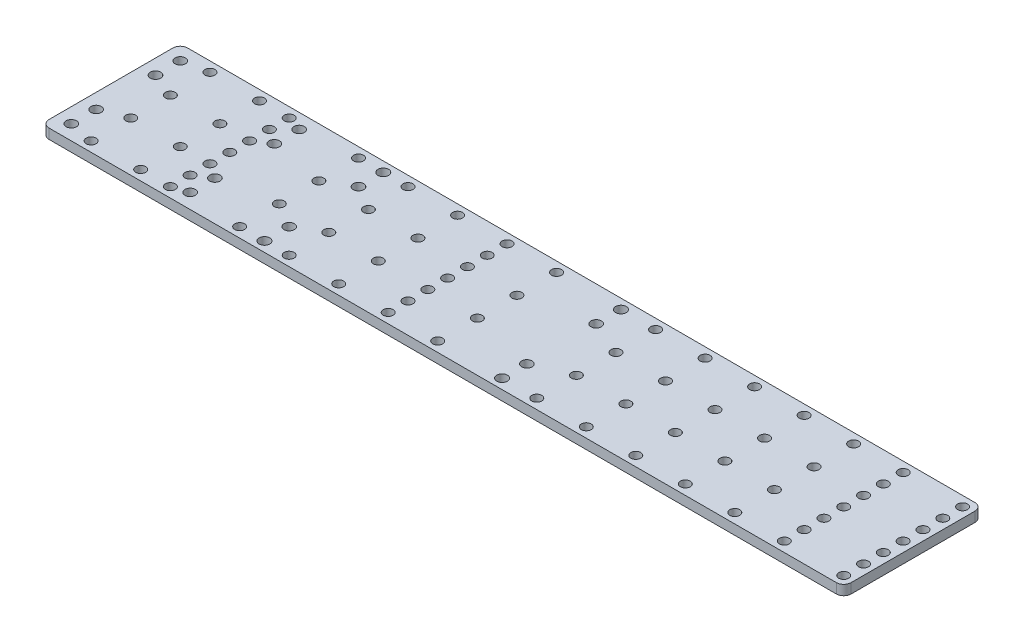
SolidWorks part; units mm, degrees
material "Thornel Mat VMA"
ref_plane "前视基准面" through (0, 0, 0) normal (0, 0, 1) x (1, 0, 0)
ref_plane "上视基准面" through (0, 0, 0) normal (0, 1, 0) x (1, 0, 0)
ref_plane "右视基准面" through (0, 0, 0) normal (1, 0, 0) x (0, 0, -1)
other "Configuration Table"
sketch "草图1" plane through (0, 0, 0) normal (0, 1, 0) x (1, 0, 0)
  line L1 (0, 0) -> (324, 0)
  line L2 (0, 0) -> (0, 56)
  line L3 (0, 56) -> (324, 56)
  line L4 (324, 0) -> (324, 56)
  dimension "D1" = 56
  dimension "D2" = 324
extrude "凸台-拉伸1" add sketch "草图1" along normal blind 4
sketch "草图2" plane through (0, 4, 0) normal (0, 1, 0) x (1, 0, 0)
  arc A4 (294, 44) -> (298, 44) centre (296, 44) ccw
  arc A5 (298, 44) -> (294, 44) centre (296, 44) ccw
  arc A8 (294, 52) -> (298, 52) centre (296, 52) ccw
  arc A9 (298, 52) -> (294, 52) centre (296, 52) ccw
  arc A12 (294, 12) -> (298, 12) centre (296, 12) ccw
  arc A13 (298, 12) -> (294, 12) centre (296, 12) ccw
  arc A16 (294, 4) -> (298, 4) centre (296, 4) ccw
  arc A17 (298, 4) -> (294, 4) centre (296, 4) ccw
  arc A20 (294, 20) -> (298, 20) centre (296, 20) ccw
  arc A21 (298, 20) -> (294, 20) centre (296, 20) ccw
  arc A24 (294, 28) -> (298, 28) centre (296, 28) ccw
  arc A25 (298, 28) -> (294, 28) centre (296, 28) ccw
  arc A28 (294, 36) -> (298, 36) centre (296, 36) ccw
  arc A29 (298, 36) -> (294, 36) centre (296, 36) ccw
  arc A32 (134, 44) -> (138, 44) centre (136, 44) ccw
  arc A33 (138, 44) -> (134, 44) centre (136, 44) ccw
  arc A36 (134, 52) -> (138, 52) centre (136, 52) ccw
  arc A37 (138, 52) -> (134, 52) centre (136, 52) ccw
  arc A40 (134, 12) -> (138, 12) centre (136, 12) ccw
  arc A41 (138, 12) -> (134, 12) centre (136, 12) ccw
  arc A44 (134, 4) -> (138, 4) centre (136, 4) ccw
  arc A45 (138, 4) -> (134, 4) centre (136, 4) ccw
  arc A48 (134, 20) -> (138, 20) centre (136, 20) ccw
  arc A49 (138, 20) -> (134, 20) centre (136, 20) ccw
  arc A52 (134, 28) -> (138, 28) centre (136, 28) ccw
  arc A53 (138, 28) -> (134, 28) centre (136, 28) ccw
  arc A56 (134, 36) -> (138, 36) centre (136, 36) ccw
  arc A57 (138, 36) -> (134, 36) centre (136, 36) ccw
  arc A60 (46, 44) -> (50, 44) centre (48, 44) ccw
  arc A61 (50, 44) -> (46, 44) centre (48, 44) ccw
  arc A64 (46, 52) -> (50, 52) centre (48, 52) ccw
  arc A65 (50, 52) -> (46, 52) centre (48, 52) ccw
  arc A68 (46, 12) -> (50, 12) centre (48, 12) ccw
  arc A69 (50, 12) -> (46, 12) centre (48, 12) ccw
  arc A72 (46, 4) -> (50, 4) centre (48, 4) ccw
  arc A73 (50, 4) -> (46, 4) centre (48, 4) ccw
  arc A76 (46, 20) -> (50, 20) centre (48, 20) ccw
  arc A77 (50, 20) -> (46, 20) centre (48, 20) ccw
  arc A80 (46, 28) -> (50, 28) centre (48, 28) ccw
  arc A81 (50, 28) -> (46, 28) centre (48, 28) ccw
  arc A84 (46, 36) -> (50, 36) centre (48, 36) ccw
  arc A85 (50, 36) -> (46, 36) centre (48, 36) ccw
extrude "切除-拉伸1" cut sketch "草图2" against normal blind 10
sketch "草图3" plane through (0, 4, 0) normal (0, 1, 0) x (1, 0, 0)
  circle A4 centre (182, 52) radius 2.15
  circle A5 centre (182, 42) radius 2.1
  circle A6 centre (182, 14) radius 2.1
  circle A7 centre (182, 4) radius 2.15
  circle A12 centre (86, 52) radius 2.15
  circle A13 centre (86, 4) radius 2.15
  circle A14 centre (86, 42) radius 2.1
  circle A15 centre (86, 14) radius 2.1
  circle A24 centre (6, 6) radius 2.1
  circle A25 centre (6, 16) radius 2.1
  circle A26 centre (6, 40) radius 2.1
  circle A27 centre (6, 50) radius 2.1
  circle A28 centre (54, 50) radius 2.1
  circle A29 centre (54, 40) radius 2.1
  circle A30 centre (54, 6) radius 2.1
  circle A31 centre (54, 16) radius 2.1
extrude "切除-拉伸2" cut sketch "草图3" against normal through all both
sketch "草图4" plane through (0, 4, 0) normal (0, 1, 0) x (1, 0, 0)
  circle A0 centre (296, 4) radius 2 construction
  circle A1 centre (296, 12) radius 2 construction
  circle A2 centre (296, 20) radius 2 construction
  circle A3 centre (296, 28) radius 2 construction
  circle A4 centre (296, 36) radius 2 construction
  circle A5 centre (296, 44) radius 2 construction
  circle A6 centre (296, 52) radius 2 construction
  circle A7 centre (296, 4) radius 2
  circle A8 centre (296, 12) radius 2 construction
  circle A9 centre (296, 20) radius 2
  circle A10 centre (296, 28) radius 2 construction
  circle A11 centre (296, 36) radius 2
  circle A12 centre (296, 44) radius 2 construction
  circle A13 centre (296, 52) radius 2
  circle A14 centre (316, 4) radius 2 construction
  circle A15 centre (316, 20) radius 2 construction
  circle A16 centre (316, 36) radius 2 construction
  circle A17 centre (316, 52) radius 2 construction
  circle A18 centre (316, 12) radius 2 construction
  circle A19 centre (316, 28) radius 2 construction
  circle A20 centre (316, 44) radius 2 construction
  circle A21 centre (276, 4) radius 2
  circle A22 centre (276, 20) radius 2
  circle A23 centre (276, 36) radius 2
  circle A24 centre (276, 52) radius 2
  circle A25 centre (276, 12) radius 2 construction
  circle A26 centre (276, 28) radius 2 construction
  circle A27 centre (276, 44) radius 2 construction
  circle A28 centre (256, 4) radius 2
  circle A29 centre (256, 20) radius 2
  circle A30 centre (256, 36) radius 2
  circle A31 centre (256, 52) radius 2
  circle A32 centre (256, 12) radius 2 construction
  circle A33 centre (256, 28) radius 2 construction
  circle A34 centre (256, 44) radius 2 construction
  circle A35 centre (236, 4) radius 2
  circle A36 centre (236, 20) radius 2
  circle A37 centre (236, 36) radius 2
  circle A38 centre (236, 52) radius 2
  circle A39 centre (236, 12) radius 2 construction
  circle A40 centre (236, 28) radius 2 construction
  circle A41 centre (236, 44) radius 2 construction
  circle A42 centre (216, 4) radius 2
  circle A43 centre (216, 20) radius 2
  circle A44 centre (216, 36) radius 2
  circle A45 centre (216, 52) radius 2
  circle A46 centre (216, 12) radius 2 construction
  circle A47 centre (216, 28) radius 2 construction
  circle A48 centre (216, 44) radius 2 construction
  circle A49 centre (196, 4) radius 2
  circle A50 centre (196, 20) radius 2
  circle A51 centre (196, 36) radius 2
  circle A52 centre (196, 52) radius 2
  circle A53 centre (196, 12) radius 2 construction
  circle A54 centre (196, 28) radius 2 construction
  circle A55 centre (196, 44) radius 2 construction
  circle A56 centre (176, 4) radius 2 construction
  circle A57 centre (176, 20) radius 2 construction
  circle A58 centre (176, 36) radius 2 construction
  circle A59 centre (176, 52) radius 2 construction
  circle A60 centre (176, 12) radius 2 construction
  circle A61 centre (176, 28) radius 2 construction
  circle A62 centre (176, 44) radius 2 construction
  circle A63 centre (156, 4) radius 2
  circle A64 centre (156, 20) radius 2
  circle A65 centre (156, 36) radius 2
  circle A66 centre (156, 52) radius 2
  circle A67 centre (156, 12) radius 2 construction
  circle A68 centre (156, 28) radius 2 construction
  circle A69 centre (156, 44) radius 2 construction
  circle A70 centre (136, 4) radius 2 construction
  circle A71 centre (136, 20) radius 2 construction
  circle A72 centre (136, 36) radius 2 construction
  circle A73 centre (136, 52) radius 2 construction
  circle A74 centre (136, 12) radius 2 construction
  circle A75 centre (136, 28) radius 2 construction
  circle A76 centre (136, 44) radius 2 construction
  circle A77 centre (116, 4) radius 2
  circle A78 centre (116, 20) radius 2
  circle A79 centre (116, 36) radius 2
  circle A80 centre (116, 52) radius 2
  circle A81 centre (116, 12) radius 2 construction
  circle A82 centre (116, 28) radius 2 construction
  circle A83 centre (116, 44) radius 2 construction
  circle A84 centre (96, 4) radius 2
  circle A85 centre (96, 20) radius 2
  circle A86 centre (96, 36) radius 2
  circle A87 centre (96, 52) radius 2
  circle A88 centre (96, 12) radius 2 construction
  circle A89 centre (96, 28) radius 2 construction
  circle A90 centre (96, 44) radius 2 construction
  circle A91 centre (76, 4) radius 2
  circle A92 centre (76, 20) radius 2
  circle A93 centre (76, 36) radius 2
  circle A94 centre (76, 52) radius 2
  circle A95 centre (76, 12) radius 2 construction
  circle A96 centre (76, 28) radius 2 construction
  circle A97 centre (76, 44) radius 2 construction
  circle A98 centre (56, 4) radius 2 construction
  circle A99 centre (56, 20) radius 2 construction
  circle A100 centre (56, 36) radius 2 construction
  circle A101 centre (56, 52) radius 2 construction
  circle A102 centre (56, 12) radius 2 construction
  circle A103 centre (56, 28) radius 2 construction
  circle A104 centre (56, 44) radius 2 construction
  circle A105 centre (36, 4) radius 2
  circle A106 centre (36, 20) radius 2
  circle A107 centre (36, 36) radius 2
  circle A108 centre (36, 52) radius 2
  circle A109 centre (36, 12) radius 2 construction
  circle A110 centre (36, 28) radius 2 construction
  circle A111 centre (36, 44) radius 2 construction
  circle A112 centre (16, 4) radius 2
  circle A113 centre (16, 20) radius 2
  circle A114 centre (16, 36) radius 2
  circle A115 centre (16, 52) radius 2
  circle A116 centre (16, 12) radius 2 construction
  circle A117 centre (16, 28) radius 2 construction
  circle A118 centre (16, 44) radius 2 construction
  arc A123 (318, 44) -> (322, 44) centre (320, 44) ccw
  arc A124 (322, 44) -> (318, 44) centre (320, 44) ccw
  arc A127 (318, 52) -> (322, 52) centre (320, 52) ccw
  arc A128 (322, 52) -> (318, 52) centre (320, 52) ccw
  arc A131 (318, 12) -> (322, 12) centre (320, 12) ccw
  arc A132 (322, 12) -> (318, 12) centre (320, 12) ccw
  arc A135 (318, 4) -> (322, 4) centre (320, 4) ccw
  arc A136 (322, 4) -> (318, 4) centre (320, 4) ccw
  arc A139 (318, 20) -> (322, 20) centre (320, 20) ccw
  arc A140 (322, 20) -> (318, 20) centre (320, 20) ccw
  arc A143 (318, 28) -> (322, 28) centre (320, 28) ccw
  arc A144 (322, 28) -> (318, 28) centre (320, 28) ccw
  arc A147 (318, 36) -> (322, 36) centre (320, 36) ccw
  arc A148 (322, 36) -> (318, 36) centre (320, 36) ccw
  dimension "D1" = 2
  dimension "D2" = 15
extrude "切除-拉伸3" cut sketch "草图4" against normal through all both
fillet "圆角1" radius 3 4 edges at (0, 2, -56) (324, 2, -56) (0, 2, 0) (324, 2, 0)
